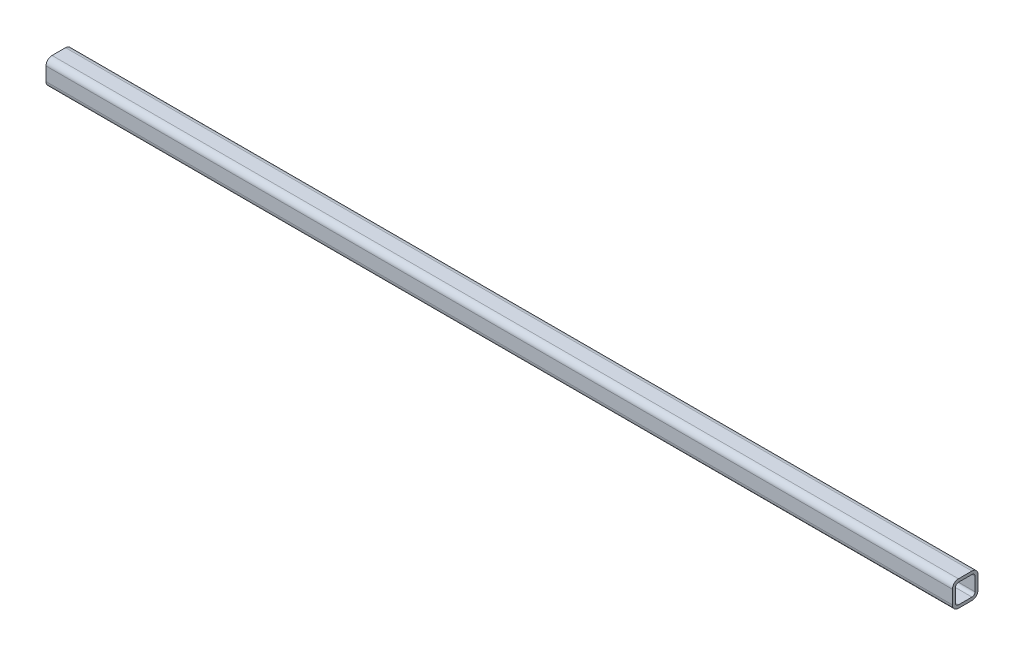
SolidWorks part; units mm, degrees
ref_plane "Alzado" through (0, 0, 0) normal (0, 0, 1) x (1, 0, 0)
ref_plane "Planta" through (0, 0, 0) normal (0, 1, 0) x (1, 0, 0)
ref_plane "Vista lateral" through (0, 0, 0) normal (1, 0, 0) x (0, 0, -1)
sketch "Croquis2" plane through (0, 0, 0) normal (0, 1, 0) x (1, 0, 0)
  line L0 (0, 0) -> (900, 0)
  dimension "D1" = 900
other "Tubo cuadrado 2 X 2 X 0.25(1)"
ref_plane "Plano1" through (0, 0, 0) normal (1, 0, 0) x (0, 0, -1)
sketch "Sketch1" plane through (0, 0, 0) normal (1, 0, 0) x (0, 0, -1)
  line L0 (-6.7, -9.7) -> (6.7, -9.7)
  line L1 (-9.7, -6.7) -> (-9.7, 6.7)
  line L2 (6.7, 9.7) -> (-6.7, 9.7)
  line L3 (9.7, 6.7) -> (9.7, -6.7)
  line L4 (-6.7, -12.7) -> (6.7, -12.7)
  line L5 (-12.7, -6.7) -> (-12.7, 6.7)
  line L6 (6.7, 12.7) -> (-6.7, 12.7)
  line L7 (12.7, 6.7) -> (12.7, -6.7)
  line L8 (0, 0) -> (9.7, 0) construction
  line L9 (0, 0) -> (0, 9.7) construction
  arc A0 (12.7, 6.7) -> (6.7, 12.7) centre (6.7, 6.7) ccw
  arc A1 (6.7, -12.7) -> (12.7, -6.7) centre (6.7, -6.7) ccw
  arc A2 (-12.7, -6.7) -> (-6.7, -12.7) centre (-6.7, -6.7) ccw
  arc A3 (-6.7, 12.7) -> (-12.7, 6.7) centre (-6.7, 6.7) ccw
  arc A4 (-6.7, 9.7) -> (-9.7, 6.7) centre (-6.7, 6.7) ccw
  arc A5 (9.7, 6.7) -> (6.7, 9.7) centre (6.7, 6.7) ccw
  arc A6 (6.7, -9.7) -> (9.7, -6.7) centre (6.7, -6.7) ccw
  arc A7 (-9.7, -6.7) -> (-6.7, -9.7) centre (-6.7, -6.7) ccw
  point P3 (0, 12.7)
  point P4 (12.7, 0)
  point P5 (0, -12.7)
  point P6 (-12.7, 0)
  point P7 (-12.7, 12.7)
  point P8 (-12.7, -12.7)
  point P33 (0, 0)
  point P35 (12.7, -12.7)
  point P36 (12.7, 12.7)
  point P37 (0, 0)
  dimension "D1" = 6
  dimension "Thickness" = 3
  dimension "V_leg" = 25.4
